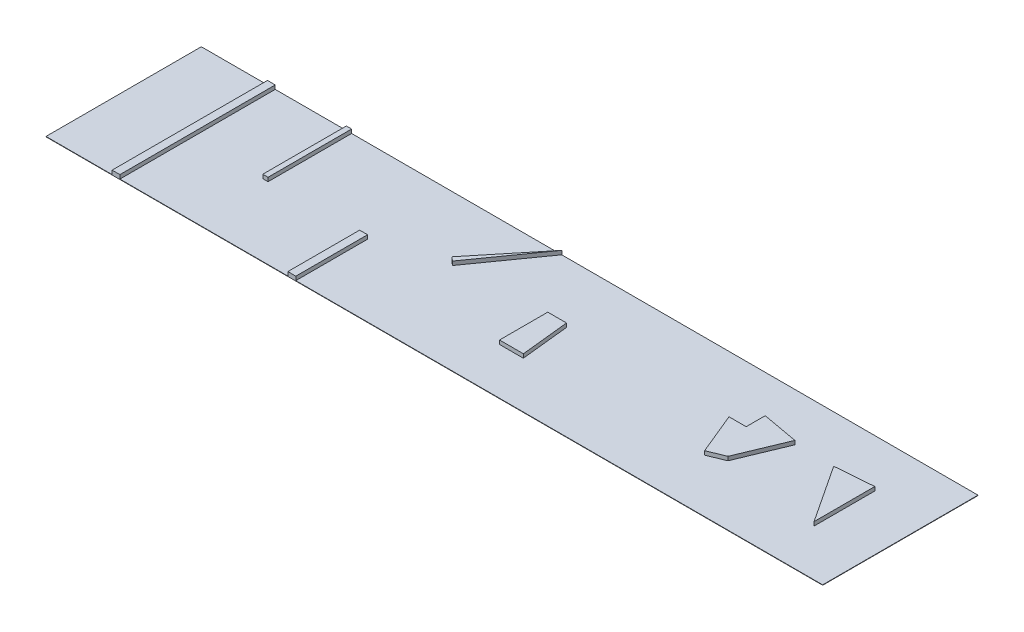
SolidWorks part; units mm, degrees
ref_plane "Front Plane" through (0, 0, 0) normal (0, 0, 1) x (1, 0, 0)
ref_plane "Top Plane" through (0, 0, 0) normal (0, 1, 0) x (1, 0, 0)
ref_plane "Right Plane" through (0, 0, 0) normal (1, 0, 0) x (0, 0, -1)
sketch "Sketch1" plane through (0, 0, 0) normal (0, 1, 0) x (1, 0, 0)
  line L1 (-122.8091, -1922.389) -> (9877.1909, -1922.389)
  line L2 (-122.8091, -1922.389) -> (-122.8091, 77.611)
  line L3 (-122.8091, 77.611) -> (9877.1909, 77.611)
  line L4 (9877.1909, -1922.389) -> (9877.1909, 77.611)
  dimension "D1" = 10000
  dimension "D2" = 2000
extrude "Boss-Extrude1" add sketch "Sketch1" along normal blind 5
sketch "Sketch2" plane through (0, 5, 0) normal (0, 1, 0) x (1, 0, 0)
  line L0 (728.7546, 77.611) -> (728.7546, -1922.389)
  line L1 (9877.1909, 77.611) -> (-122.8091, 77.611) construction
  line L2 (-122.8091, -1922.389) -> (9877.1909, -1922.389) construction
  line L3 (728.7546, -1922.389) -> (828.7546, -1922.389)
  line L4 (828.7546, -1922.389) -> (828.7546, 77.611)
  line L5 (828.7546, 77.611) -> (728.7546, 77.611)
  line L6 (1744.3674, 77.611) -> (1744.3674, -998.1355)
  line L7 (1744.3674, -998.1355) -> (1812.0034, -998.1355)
  line L8 (1812.0034, -998.1355) -> (1812.0034, 77.611)
  line L9 (1812.0034, 77.611) -> (1744.3674, 77.611)
  line L10 (2991.3048, -1922.389) -> (2991.3048, -998.1355)
  line L11 (2991.3048, -998.1355) -> (3093.5704, -998.1355)
  line L12 (3093.5704, -998.1355) -> (3093.5704, -1922.389)
  line L13 (3093.5704, -1922.389) -> (2991.3048, -1922.389)
  line L14 (4517.9847, 77.611) -> (3882.4768, -701.6868)
  line L15 (3882.4768, -701.6868) -> (3933.6096, -745.515)
  line L16 (3933.6096, -745.515) -> (4517.9847, 77.611)
  line L17 (5358.0239, -701.6868) -> (5116.9692, -701.6868)
  line L18 (5116.9692, -701.6868) -> (5116.9692, -1322.5854)
  line L19 (5116.9692, -1322.5854) -> (5423.7661, -1322.5854)
  line L20 (5423.7661, -1322.5854) -> (5358.0239, -701.6868)
  line L21 (7671.5649, -701.6868) -> (7450.6711, -701.6868)
  line L22 (7450.6711, -701.6868) -> (7671.5649, -1236.8283)
  line L23 (7671.5649, -1236.8283) -> (7884.7017, -1148.8505)
  line L24 (7884.7017, -1148.8505) -> (8137.6132, -540.3815)
  line L25 (8137.6132, -540.3815) -> (7671.5649, -456.7237)
  line L26 (7671.5649, -456.7237) -> (7671.5649, -701.6868)
  line L27 (9166.6581, -540.3815) -> (9166.6581, -1322.5854)
  line L28 (9166.6581, -1322.5854) -> (8675.8953, -579.2053)
  line L29 (8675.8953, -579.2053) -> (9166.6581, -540.3815)
  dimension "D1" = 100
extrude "Boss-Extrude2" add sketch "Sketch2" along normal blind 50
